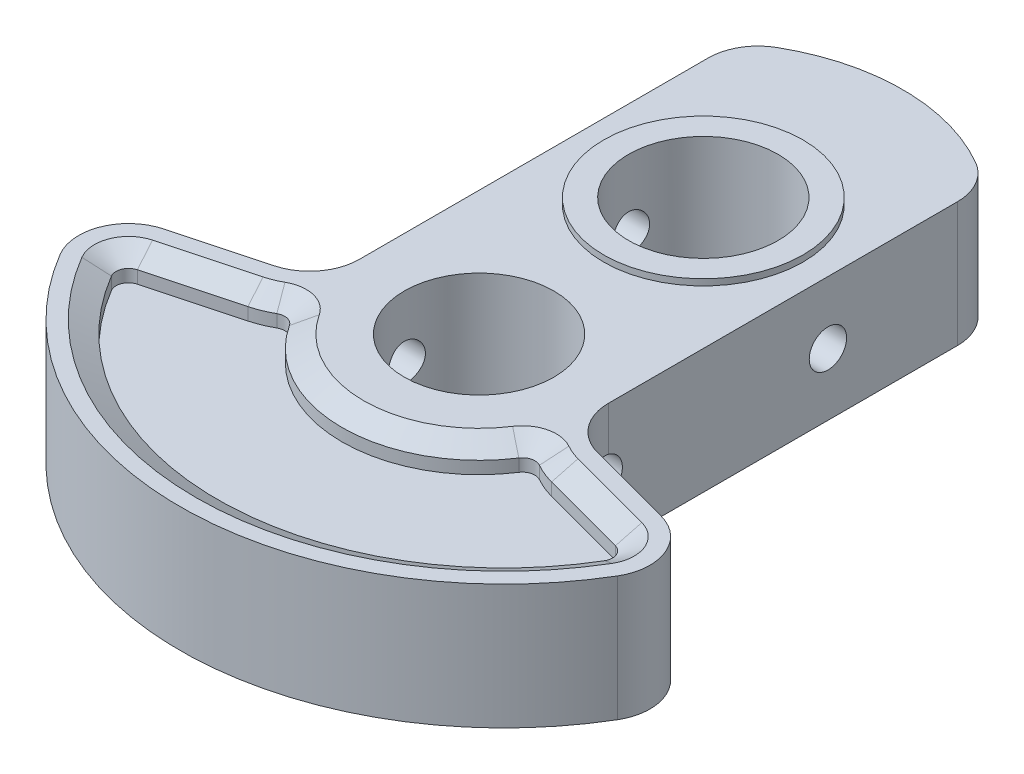
SolidWorks part; units mm, degrees
ref_plane "Front Plane" through (0, 0, 0) normal (0, 0, 1) x (1, 0, 0)
ref_plane "Top Plane" through (0, 0, 0) normal (0, 1, 0) x (1, 0, 0)
ref_plane "Right Plane" through (0, 0, 0) normal (1, 0, 0) x (0, 0, -1)
sketch "Sketch1" plane through (0, 0, 0) normal (0, 1, 0) x (1, 0, 0)
  line L0 (0, 48.0841) -> (0, -26.2277) construction
  line L1 (-10, 30.49) -> (-10, -2.6795)
  line L2 (10, 30.49) -> (10, -2.6795)
  line L3 (-10, 48.0841) -> (-10, -26.2277) construction
  line L4 (10, 48.0841) -> (10, -26.2277) construction
  line L5 (0, 0) -> (-24.5447, -6.5767) construction
  line L6 (0, 0) -> (24.5447, -6.5767) construction
  line L7 (-10, -2.6795) -> (-24.5447, -6.5767)
  line L8 (10, -2.6795) -> (24.5447, -6.5767)
  arc A1 (10, 30.49) -> (-10, 30.49) centre (0, 18) ccw
  arc A2 (-24.5447, -6.5767) -> (24.5447, -6.5767) centre (0, 2) ccw
  dimension "D5" = 26
  dimension "D2" = 18
  dimension "D3" = 10
  dimension "D6" = 75
  dimension "D7" = 75
  dimension "D4" = 10
extrude "Boss-Extrude1" add sketch "Sketch1" along normal mid plane 10
fillet "Fillet1" radius 4 6 edges at (24.5447, 0, 6.5767) (10, 0, 2.6795) (-24.5447, 0, 6.5767) (-10, 0, 2.6795) (-10, 0, -30.49) (10, 0, -30.49)
sketch "Sketch3" plane through (0, -5, 0) normal (0, -1, 0) x (1, 0, 0)
  circle A0 centre (0, 0) radius 8
  dimension "D1" = 16
extrude "Boss-Extrude2" add sketch "Sketch3" along normal mid plane 1
sketch "Sketch4" plane through (0, 5, 0) normal (0, 1, 0) x (1, 0, 0)
  circle A0 centre (0, 18) radius 8
  dimension "D1" = 16
  dimension "D2" = 18
extrude "Boss-Extrude3" add sketch "Sketch4" along normal mid plane 1
sketch "Sketch5" plane through (0, -5.5, 0) normal (0, -1, 0) x (1, 0, 0)
  circle A0 centre (0, 0) radius 6
  circle A2 centre (0, -18) radius 6
  dimension "D1" = 12
  dimension "D2" = 12
extrude "Cut-Extrude3" cut sketch "Sketch5" against normal through all
sketch "Sketch6" plane through (0, 5, 0) normal (0, 1, 0) x (1, 0, 0)
  line L11 (12.1883, -6.3717) -> (19.1869, -8.2469)
  line L12 (-19.1869, -8.2469) -> (-12.1883, -6.3717)
  line L13 (12.1883, -6.3717) -> (19.1869, -8.2469)
  line L14 (-19.1869, -8.2469) -> (-12.1883, -6.3717)
  arc A20 (-9.2082, -6.0173) -> (9.2082, -6.0173) centre (0, 0) ccw
  arc A21 (9.2082, -6.0173) -> (10.5397, -5.6951) centre (10.0453, -6.5644) cw
  arc A22 (-9.2082, -6.0173) -> (-10.5397, -5.6951) centre (-10.0453, -6.5644) ccw
  arc A25 (7, 0.3898) -> (12.1883, -6.3717) centre (14, 0.3898) ccw
  arc A26 (-12.1883, -6.3717) -> (-7, 0.3898) centre (-14, 0.3898) ccw
  arc A27 (19.7884, -9.7225) -> (19.1869, -8.2469) centre (18.9281, -9.2129) ccw
  arc A28 (-19.1869, -8.2469) -> (-19.7884, -9.7225) centre (-18.9281, -9.2129) ccw
  arc A29 (-19.7884, -9.7225) -> (19.7884, -9.7225) centre (0, 2) ccw
  arc A30 (10.5397, -5.6951) -> (12.1883, -6.3717) centre (14, 0.3898) ccw
  arc A31 (-12.1883, -6.3717) -> (-10.5397, -5.6951) centre (-14, 0.3898) ccw
  arc A32 (19.7884, -9.7225) -> (19.1869, -8.2469) centre (18.9281, -9.2129) ccw
  arc A33 (-19.1869, -8.2469) -> (-19.7884, -9.7225) centre (-18.9281, -9.2129) ccw
  arc A34 (-19.7884, -9.7225) -> (19.7884, -9.7225) centre (0, 2) ccw
  dimension "D2" = 22
  dimension "D3" = 1
  dimension "D1" = 3
extrude "Cut-Extrude4" cut sketch "Sketch6" against normal blind 2
chamfer "Chamfer1" distance 1 angle 60 10 edges at (11.3424, 5, 6.0861) (9.8101, 5, 5.5924) (15.6876, 5, 7.3093) (0, 5, 11) (19.8541, 5, 8.8354) (-9.8101, 5, 5.5924) (0, 5, 21) (-11.3424, 5, 6.0861) (-19.8541, 5, 8.8354) (-15.6876, 5, 7.3093)
mirror "Mirror5" about plane through (0, 0, 0) normal (0, 1, 0) of "Cut-Extrude4"
chamfer "Chamfer2" distance 1 angle 60 10 edges at (-11.3424, -5, 6.0861) (-15.6876, -5, 7.3093) (-9.8101, -5, 5.5924) (-19.8541, -5, 8.8354) (0, -5, 11) (0, -5, 21) (9.8101, -5, 5.5924) (19.8541, -5, 8.8354) (11.3424, -5, 6.0861) (15.6876, -5, 7.3093)
sketch "Sketch7" plane through (0, 0, 0) normal (1, 0, 0) x (0, 0, -1)
  circle A0 centre (0, 0) radius 1.5
  circle A1 centre (18, 0) radius 1.5
  dimension "D1" = 3
  dimension "D2" = 3
  dimension "D3" = 18
extrude "Cut-Extrude5" cut sketch "Sketch7" against normal through all both and the other way through all
